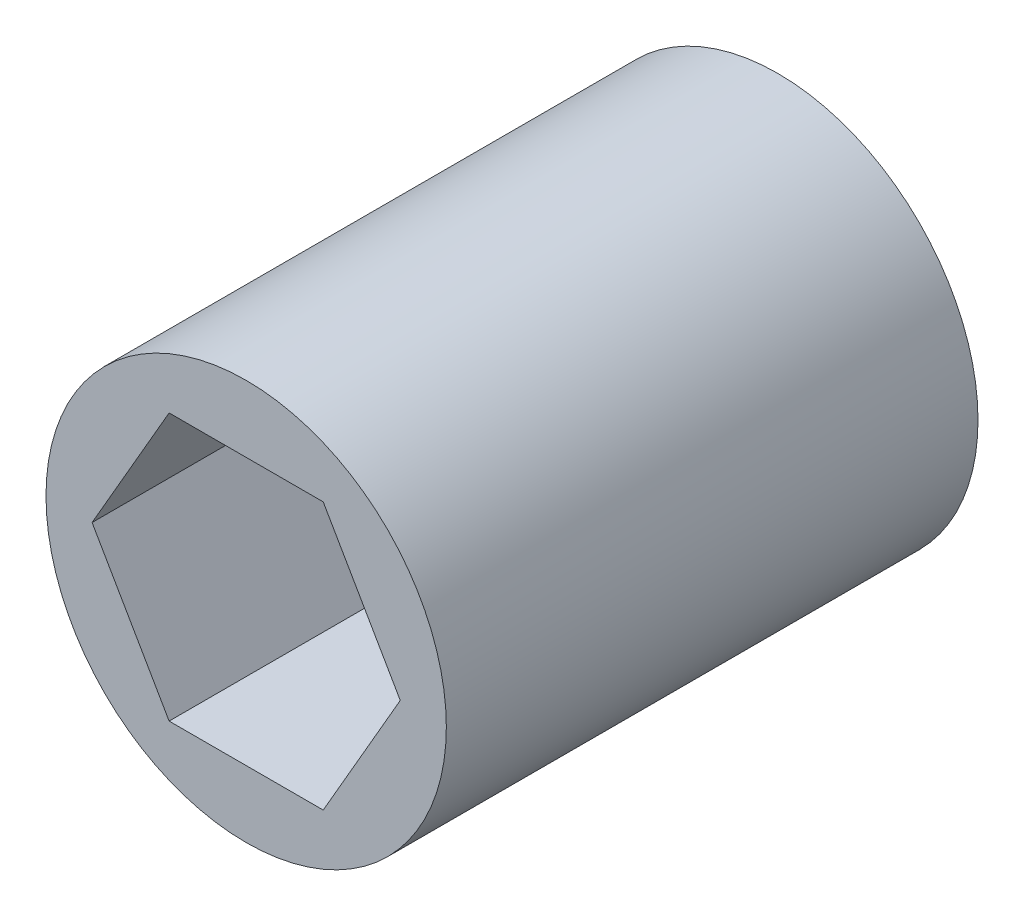
SolidWorks part; units mm, degrees
material "Nylon 101"
ref_plane "Front Plane" through (0, 0, 0) normal (0, 0, 1) x (1, 0, 0)
ref_plane "Top Plane" through (0, 0, 0) normal (0, 1, 0) x (1, 0, 0)
ref_plane "Right Plane" through (0, 0, 0) normal (1, 0, 0) x (0, 0, -1)
sketch "Sketch1" plane through (0, 0, 0) normal (0, 0, 1) x (1, 0, 0)
  line L1 (-3.6662, 6.35) -> (-7.3323, 0)
  line L2 (-7.3323, 0) -> (-3.6662, -6.35)
  line L3 (-3.6662, -6.35) -> (3.6662, -6.35)
  line L4 (3.6662, -6.35) -> (7.3323, 0)
  line L5 (7.3323, 0) -> (3.6662, 6.35)
  line L6 (3.6662, 6.35) -> (-3.6662, 6.35)
  circle A0 centre (0, 0) radius 9.525
  circle A1 centre (0, 0) radius 6.35 construction
  point P3 (0, 6.35)
  dimension "D1" = 19.05
  dimension "D2" = 12.7
extrude "Boss-Extrude1" add sketch "Sketch1" along normal blind 25.2984
